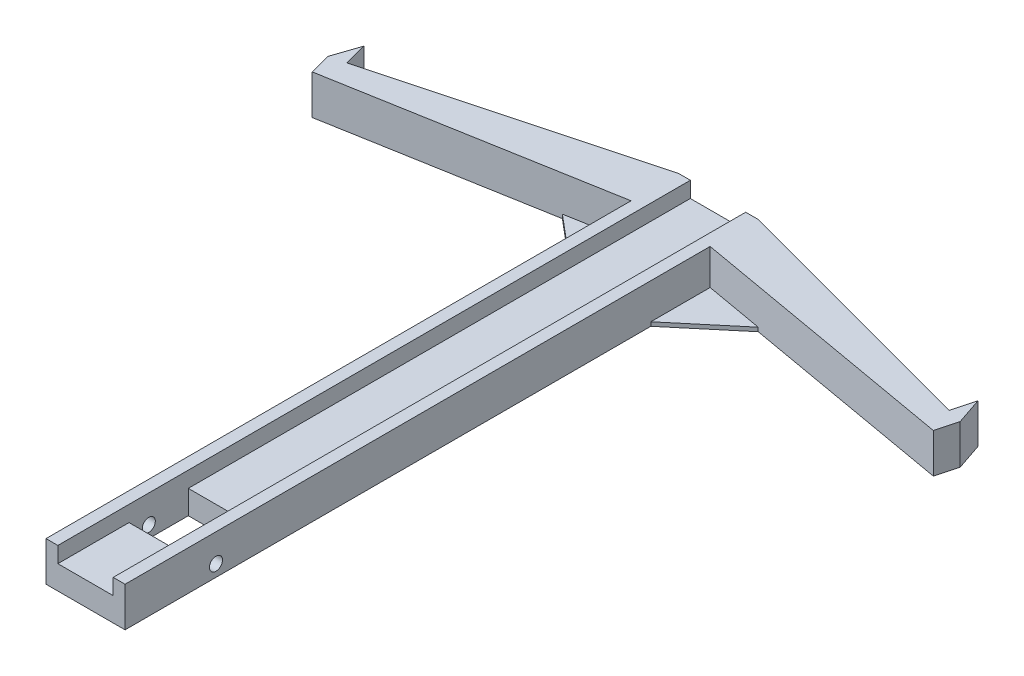
SolidWorks part; units mm, degrees
ref_plane "Front Plane" through (0, 0, 0) normal (0, 0, 1) x (1, 0, 0)
ref_plane "Top Plane" through (0, 0, 0) normal (0, 1, 0) x (1, 0, 0)
ref_plane "Right Plane" through (0, 0, 0) normal (1, 0, 0) x (0, 0, -1)
sketch "Sketch1" plane through (0, 0, 0) normal (0, 1, 0) x (1, 0, 0)
  line L0 (-10, 80) -> (-80, 61.2436)
  line L1 (-10, 80) -> (10, 80)
  line L2 (-10, 68) -> (-10, -80)
  line L3 (-10, -80) -> (10, -80)
  line L4 (10, 68) -> (10, -80)
  line L5 (0, 0) -> (10, -80) construction
  line L6 (-10, -80) -> (0, 0) construction
  line L7 (-80, 61.2436) -> (-78.5706, 55.9091)
  line L8 (-78.5706, 55.9091) -> (-10, 68)
  line L10 (10, 80) -> (80, 61.2436)
  line L11 (80, 61.2436) -> (78.5706, 55.9091)
  line L12 (78.5706, 55.9091) -> (10, 68)
  point P0 (0, 0)
  point P12 (10, 67.7231)
  dimension "D1" = 160
  dimension "D2" = 20
  dimension "D3" = 75
  dimension "D4" = 75
  dimension "D5" = 70
  dimension "D6" = 70
  dimension "D7" = 80
  dimension "D8" = 80
  dimension "D9" = 0
  dimension "D10" = 12
extrude "Boss-Extrude1" add sketch "Sketch1" along normal blind 10
sketch "Sketch2" plane through (0, 10, 0) normal (0, 1, 0) x (1, 0, 0)
  line L0 (10, 80) -> (-10, 80) construction
  line L1 (-7, 80) -> (7, 80)
  line L2 (-7, 80) -> (-7, -80)
  line L3 (-7, -80) -> (7, -80)
  line L4 (7, 80) -> (7, -80)
  line L5 (-10, -80) -> (10, -80) construction
  line L6 (-10, 68) -> (-10, -80) construction
  line L7 (10, -80) -> (10, 68) construction
  dimension "D1" = 3
  dimension "D2" = 3
extrude "Cut-Extrude1" cut sketch "Sketch2" against normal blind 4
sketch "Sketch3" plane through (0, 10, 0) normal (0, 1, 0) x (1, 0, 0)
  line L2 (77.6892, 68.0744) -> (76.1363, 62.2788)
  line L3 (80, 61.2436) -> (10, 80) construction
  line L4 (76.1363, 62.2788) -> (80, 61.2436)
  line L7 (-77.6892, 68.0744) -> (-76.1363, 62.2788)
  line L8 (-10, 80) -> (-80, 61.2436) construction
  line L9 (-76.1363, 62.2788) -> (-80, 61.2436)
  line L10 (77.6892, 68.0744) -> (80, 61.2436)
  line L11 (-77.6892, 68.0744) -> (-80, 61.2436)
extrude "Boss-Extrude2" add sketch "Sketch3" against normal blind 10
sketch "Sketch4" plane through (0, 6, 0) normal (0, 1, 0) x (1, 0, 0)
  line L0 (-7, 80) -> (-7, -80) construction
  line L1 (-7, -47) -> (7, -47)
  line L2 (-7, -47) -> (-7, -62)
  line L3 (-7, -62) -> (7, -62)
  line L4 (7, -47) -> (7, -62)
  line L5 (7, -80) -> (7, 80) construction
  line L6 (-7, -80) -> (7, -80) construction
  dimension "D1" = 18
  dimension "D2" = 15
extrude "Cut-Extrude2" cut sketch "Sketch4" against normal blind 10
sketch "Sketch5" plane through (7, 0, 0) normal (-1, 0, 0) x (0, 0, 1)
  line L0 (62, 0) -> (47, 0) construction
  line L1 (62, 0) -> (62, 6) construction
  circle A0 centre (57, 3) radius 1.65
  dimension "D1" = 3.3
  dimension "D2" = 3
  dimension "D3" = 5
extrude "Cut-Extrude3" cut sketch "Sketch5" against normal blind 10 and the other way blind 20
sketch "Sketch6" plane through (0, 0, 0) normal (0, -1, 0) x (1, 0, 0)
  line L0 (-24.7721, -65.3953) -> (-10, -53)
  line L1 (-78.5706, -55.9091) -> (-10, -68) construction
  line L2 (-10, -68) -> (-10, 80) construction
  line L3 (-10, -53) -> (-10, -68)
  line L4 (-10, -68) -> (-24.7721, -65.3953)
  line L5 (10, -53) -> (24.7721, -65.3953)
  line L6 (10, 80) -> (10, -68) construction
  line L7 (10, -68) -> (78.5706, -55.9091) construction
  line L8 (24.7721, -65.3953) -> (10, -68)
  line L9 (10, -68) -> (10, -53)
  dimension "D1" = 15
  dimension "D2" = 15
  dimension "D3" = 15
  dimension "D4" = 15
extrude "Boss-Extrude3" add sketch "Sketch6" against normal blind 1
